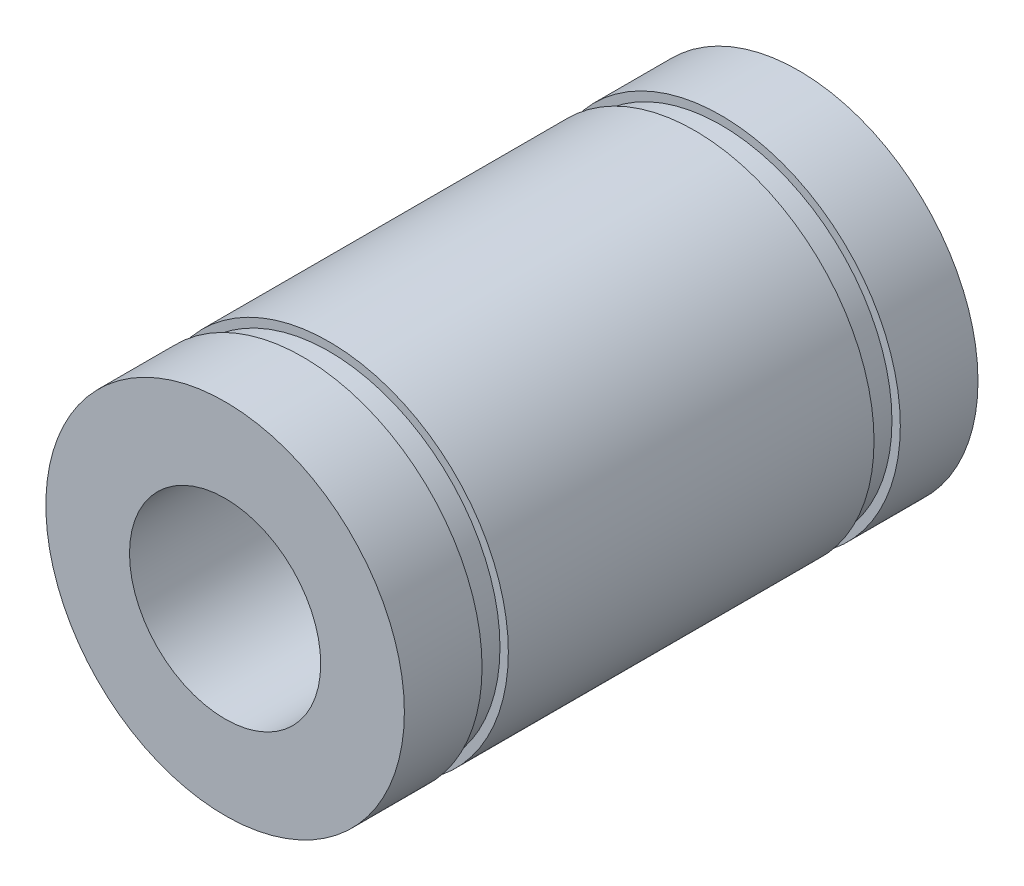
SolidWorks part; units mm, degrees
ref_plane "前视基准面" through (0, 0, 0) normal (0, 0, 1) x (1, 0, 0)
ref_plane "上视基准面" through (0, 0, 0) normal (0, 1, 0) x (1, 0, 0)
ref_plane "右视基准面" through (0, 0, 0) normal (1, 0, 0) x (0, 0, -1)
sketch "草图1" plane through (0, 0, 0) normal (0, 0, 1) x (1, 0, 0)
  circle A0 centre (0, 0) radius 7.5
  circle A1 centre (0, 0) radius 4
  dimension "D1" = 8
  dimension "D2" = 15
extrude "凸台-拉伸1" add sketch "草图1" against normal mid plane 24
sketch "草图2" plane through (0, 0, 0) normal (1, 0, 0) x (0, 0, -1)
  line L0 (-1000, 0) -> (49000, 0) construction
  line L1 (0, -992) -> (0, 49008) construction
  line L2 (12, 7.5) -> (-12, 7.5) construction
  line L4 (-8.75, 7.5) -> (-7.65, 7.5)
  line L5 (-8.75, 7.5) -> (-8.75, 7.15)
  line L6 (-8.75, 7.15) -> (-7.65, 7.15)
  line L7 (-7.65, 7.5) -> (-7.65, 7.15)
  point P8 (0, 7.5)
  dimension "D1" = 1.1
  dimension "D2" = 0.35
  dimension "D3" = 17.5
revolve "切除-旋转1" cut sketch "草图2" angle 360 about L0
mirror "镜向1" about plane through (0, 0, 0) normal (0, 0, 1) of "切除-旋转1"
